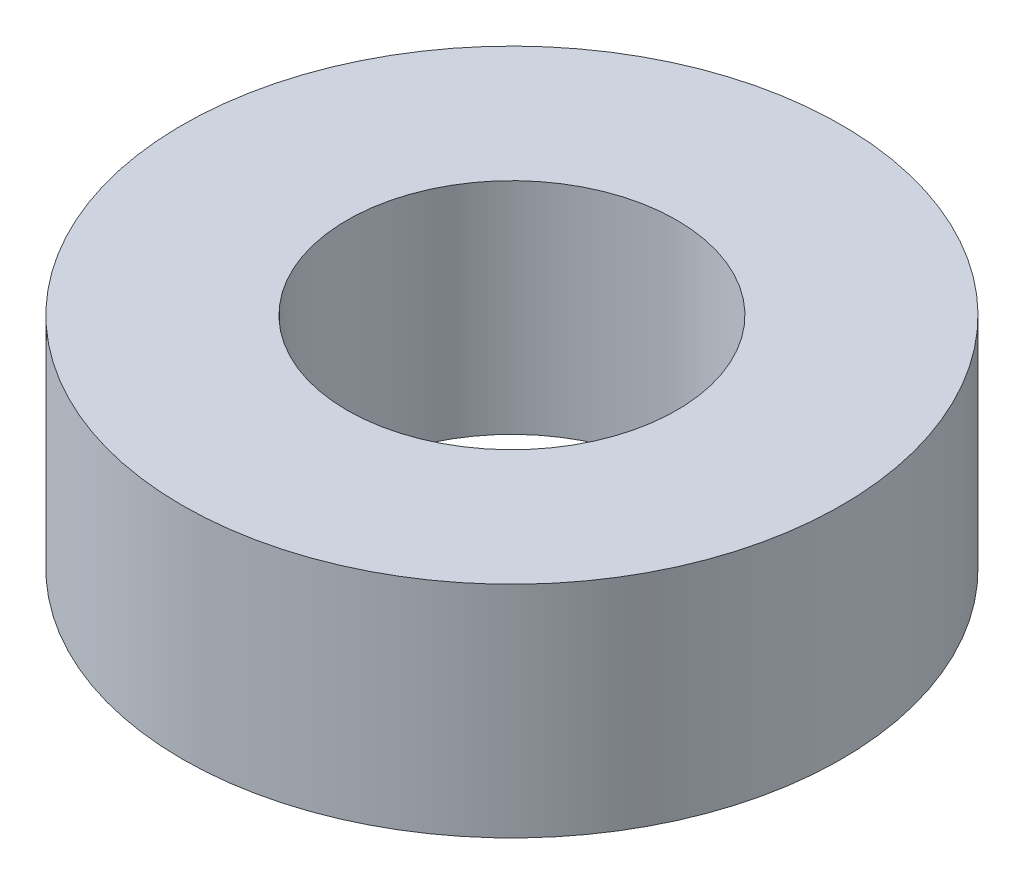
SolidWorks part; units mm, degrees
ref_plane "Спереди" through (0, 0, 0) normal (0, 0, 1) x (1, 0, 0)
ref_plane "Сверху" through (0, 0, 0) normal (0, 1, 0) x (1, 0, 0)
ref_plane "Справа" through (0, 0, 0) normal (1, 0, 0) x (0, 0, -1)
sketch "Эскиз1" plane through (0, 0, 0) normal (0, 1, 0) x (1, 0, 0)
  circle A0 centre (0, 0) radius 30
  dimension "D1" = 60
extrude "Бобышка-Вытянуть1" add sketch "Эскиз1" along normal blind 20
sketch "Эскиз2" plane through (0, 20, 0) normal (0, 1, 0) x (1, 0, 0)
  circle A0 centre (0, 0) radius 15
  dimension "D1" = 30
extrude "Вырез-Вытянуть1" cut sketch "Эскиз2" against normal blind 20
